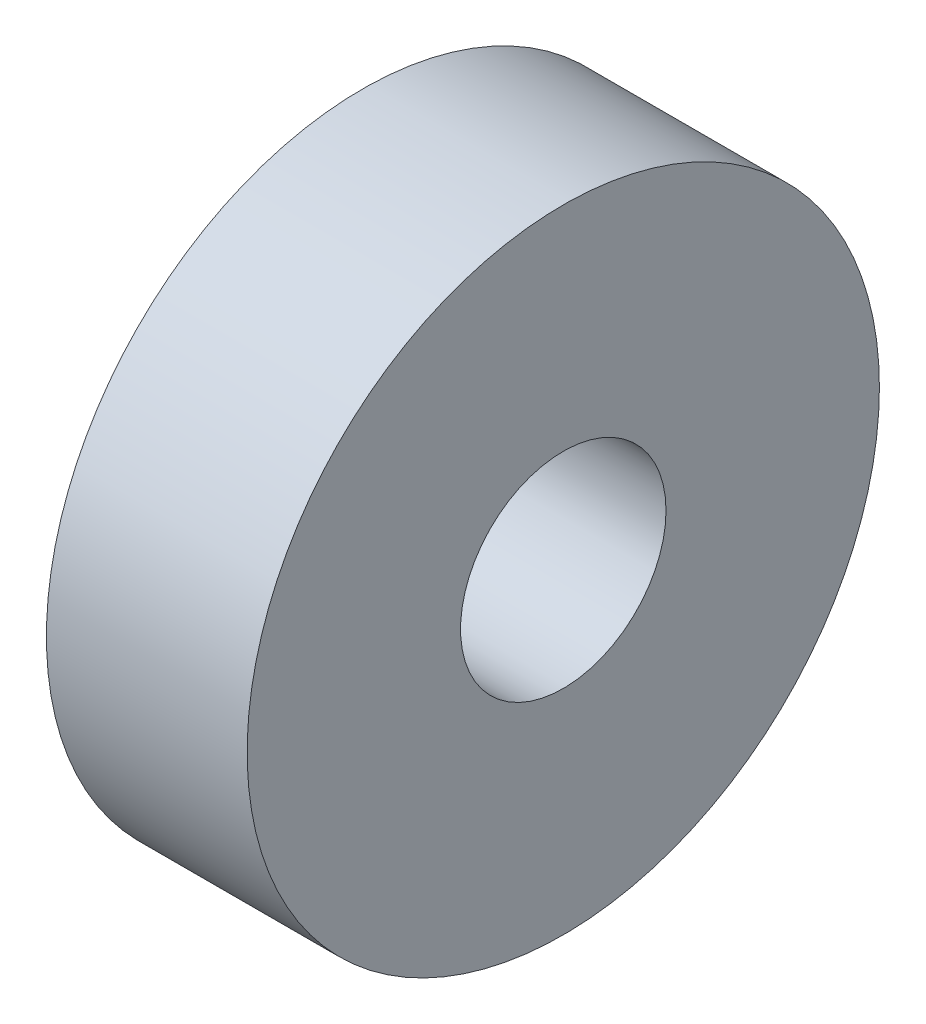
SolidWorks part; units mm, degrees
ref_plane "Front Plane" through (0, 0, 0) normal (0, 0, 1) x (1, 0, 0)
ref_plane "Top Plane" through (0, 0, 0) normal (0, 1, 0) x (1, 0, 0)
ref_plane "Right Plane" through (0, 0, 0) normal (1, 0, 0) x (0, 0, -1)
sketch "Sketch1" plane through (0, 0, 0) normal (1, 0, 0) x (0, 0, -1)
  circle A0 centre (0, 0) radius 10
  circle A1 centre (0, 0) radius 3.25
  dimension "D1" = 6.5
  dimension "D2" = 20
extrude "Boss-Extrude1" add sketch "Sketch1" along normal blind 6.35
